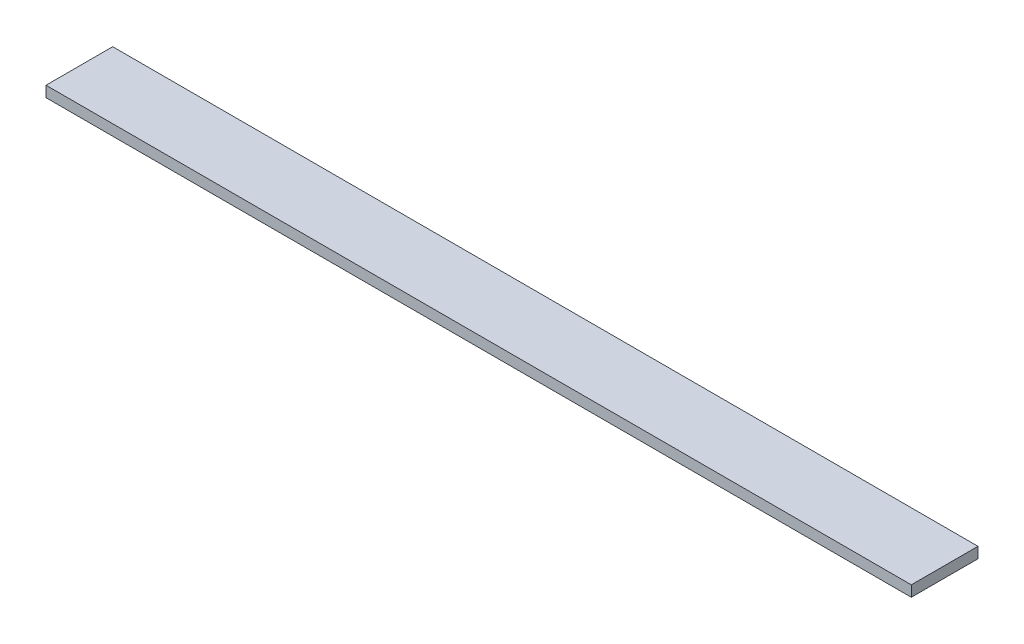
SolidWorks part; units mm, degrees
material "Pine"
ref_plane "Front Plane" through (0, 0, 0) normal (0, 0, 1) x (1, 0, 0)
ref_plane "Top Plane" through (0, 0, 0) normal (0, 1, 0) x (1, 0, 0)
ref_plane "Right Plane" through (0, 0, 0) normal (1, 0, 0) x (0, 0, -1)
sketch "Sketch1" plane through (0, 0, 0) normal (0, 1, 0) x (1, 0, 0)
  line L1 (-1312.2559, 579.5101) -> (1735.7441, 579.5101)
  line L2 (-1312.2559, 579.5101) -> (-1312.2559, 344.5601)
  line L3 (-1312.2559, 344.5601) -> (1735.7441, 344.5601)
  line L4 (1735.7441, 579.5101) -> (1735.7441, 344.5601)
  dimension "D1" = 3048
  dimension "D2" = 234.95
extrude "Boss-Extrude1" add sketch "Sketch1" along normal blind 38.1
